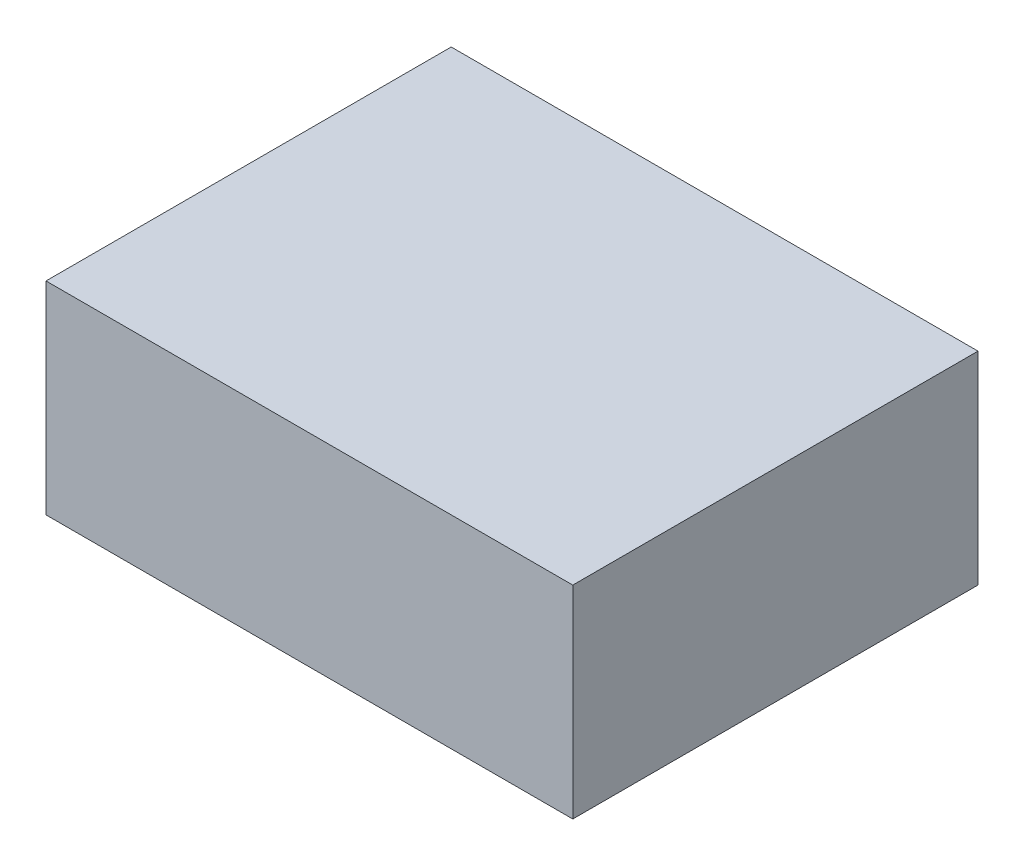
SolidWorks part; units mm, degrees
ref_plane "Front Plane" through (0, 0, 0) normal (0, 0, 1) x (1, 0, 0)
ref_plane "Top Plane" through (0, 0, 0) normal (0, 1, 0) x (1, 0, 0)
ref_plane "Right Plane" through (0, 0, 0) normal (1, 0, 0) x (0, 0, -1)
sketch "Sketch1" plane through (0, 0, 0) normal (0, 1, 0) x (1, 0, 0)
  line L1 (-32.5, -25) -> (32.5, -25)
  line L2 (-32.5, -25) -> (-32.5, 25)
  line L3 (-32.5, 25) -> (32.5, 25)
  line L4 (32.5, -25) -> (32.5, 25)
  line L5 (-32.5, -25) -> (32.5, 25) construction
  line L6 (-32.5, 25) -> (32.5, -25) construction
  point P0 (0, 0)
  dimension "D1" = 65
  dimension "D2" = 50
extrude "Boss-Extrude1" add sketch "Sketch1" along normal blind 25
sketch "Sketch2" plane through (0, 0, 0) normal (0, -1, 0) x (1, 0, 0)
  line L0 (-32.5, -25) -> (-32.5, 25) construction
  circle A0 centre (-17.5, 0) radius 5
  circle A1 centre (-17.5, 0) radius 10
  point P4 (-19.8871, 0)
  point P5 (-18.7294, -2.2424)
  dimension "D1" = 10
  dimension "D3" = 15
  dimension "D2" = 5
extrude "Boss-Extrude2" add sketch "Sketch2" along normal blind 10
